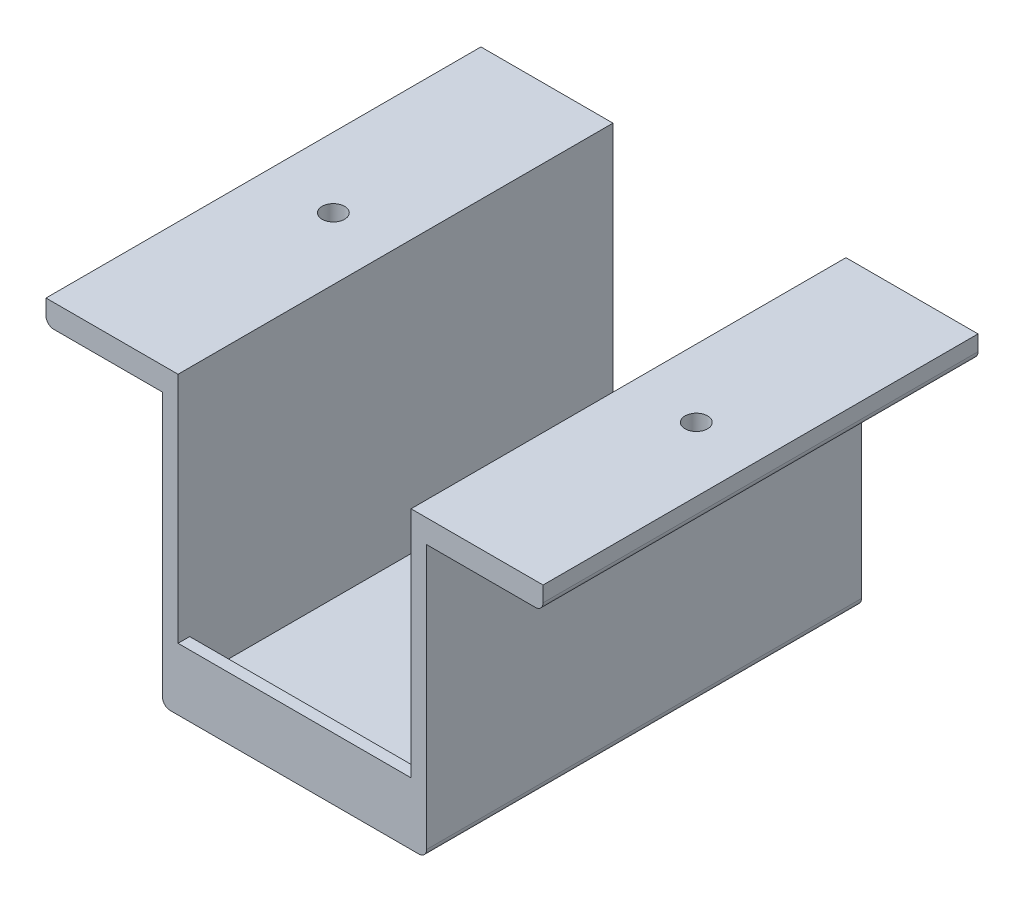
SolidWorks part; units mm, degrees
material "ABS"
ref_plane "Front Plane" through (0, 0, 0) normal (0, 0, 1) x (1, 0, 0)
ref_plane "Top Plane" through (0, 0, 0) normal (0, 1, 0) x (1, 0, 0)
ref_plane "Right Plane" through (0, 0, 0) normal (1, 0, 0) x (0, 0, -1)
sketch "Sketch2" plane through (0, 0, 0) normal (0, 1, 0) x (1, 0, 0)
  line L1 (0, 40.8875) -> (34, 40.8875)
  line L2 (0, 40.8875) -> (0, -15.1125)
  line L3 (0, -15.1125) -> (34, -15.1125)
  line L4 (34, 40.8875) -> (34, -15.1125)
  dimension "D1" = 34
  dimension "D2" = 56
extrude "Boss-Extrude1" add sketch "Sketch2" along normal blind 3
sketch "Sketch3" plane through (0, 3, 0) normal (0, 1, 0) x (1, 0, 0)
  line L0 (34, -15.1125) -> (34, 40.8875) construction
  line L1 (0, 40.8875) -> (2, 40.8875)
  line L2 (0, 40.8875) -> (0, -15.1125)
  line L3 (0, -15.1125) -> (2, -15.1125)
  line L4 (2, 40.8875) -> (2, -15.1125)
  line L13 (34, 40.8875) -> (32, 40.8875)
  line L14 (34, 40.8875) -> (34, -15.1125)
  line L15 (34, -15.1125) -> (32, -15.1125)
  line L16 (32, 40.8875) -> (32, -15.1125)
  dimension "D1" = 2
  dimension "D2" = 2
  dimension "D3" = 56
  dimension "D4" = 0
extrude "Boss-Extrude2" add sketch "Sketch3" along normal blind 35
sketch "Sketch4" plane through (34, 0, 0) normal (1, 0, 0) x (0, 0, -1)
  line L0 (-15.1125, 38) -> (40.8875, 38) construction
  line L1 (-15.1125, 38) -> (40.8875, 38)
  line L2 (-15.1125, 38) -> (-15.1125, 35.0081)
  line L3 (-15.1125, 35.0081) -> (40.8875, 35.0081)
  line L4 (40.8875, 38) -> (40.8875, 35.0081)
  dimension "D1" = 0
  dimension "D2" = 56
extrude "Boss-Extrude3" add sketch "Sketch4" along normal blind 15
sketch "Sketch5" plane through (0, 0, 0) normal (-1, 0, 0) x (0, 0, 1)
  line L0 (-40.8875, 38) -> (15.1125, 38) construction
  line L1 (-40.8875, 38) -> (15.1125, 38)
  line L2 (-40.8875, 38) -> (-40.8875, 35.0081)
  line L3 (-40.8875, 35.0081) -> (15.1125, 35.0081)
  line L4 (15.1125, 38) -> (15.1125, 35.0081)
  line L5 (-40.8875, 38) -> (-40.8875, 0) construction
  dimension "D1" = 0
  dimension "D2" = 56
  dimension "D3" = 0
extrude "Boss-Extrude4" add sketch "Sketch5" along normal blind 15
sketch "Sketch6" plane through (0, 3, 0) normal (0, 1, 0) x (1, 0, 0)
  line L0 (32, 40.8875) -> (2, 40.8875) construction
  line L5 (32, 40.8875) -> (2, 40.8875)
  line L6 (32, 40.8875) -> (32, 38.8875)
  line L7 (32, 38.8875) -> (2, 38.8875)
  line L8 (2, 40.8875) -> (2, 38.8875)
  line L10 (2, -13.6125) -> (32, -13.6125)
  line L11 (2, -13.6125) -> (2, -15.1125)
  line L12 (2, -15.1125) -> (32, -15.1125)
  line L13 (32, -13.6125) -> (32, -15.1125)
  dimension "D1" = 30
  dimension "D2" = 0
  dimension "D3" = 2
  dimension "D4" = 1.5
extrude "Boss-Extrude5" add sketch "Sketch6" along normal blind 5
sketch "Sketch8" plane through (0, 38, 0) normal (0, 1, 0) x (1, 0, 0)
  line L0 (49, 40.8875) -> (49, -15.1125) construction
  line L1 (-15, -15.1125) -> (-6.0021, -15.1125) construction
  line L2 (-15, -15.1125) -> (-15, 12.8875) construction
  line L3 (-15, 12.8875) -> (-6.0021, 12.8875) construction
  line L4 (-6.0021, -15.1125) -> (-6.0021, 12.8875) construction
  line L5 (49, -15.1125) -> (40.7304, -15.1125) construction
  line L6 (49, -15.1125) -> (49, 12.8875) construction
  line L7 (49, 12.8875) -> (40.7304, 12.8875) construction
  line L8 (40.7304, -15.1125) -> (40.7304, 12.8875) construction
  circle A0 centre (-6.0021, 12.8875) radius 1.45
  circle A1 centre (40.7304, 12.8875) radius 1.45
  dimension "D1" = 2.9
  dimension "D2" = 2.9
  dimension "D3" = 28
  dimension "D4" = 8.9979
  dimension "D5" = 28
  dimension "D6" = 0
extrude "Cut-Extrude1" cut sketch "Sketch8" against normal through all
fillet "Fillet1" radius 1 4 edges at (49, 35.0081, -12.8875) (-15, 35.0081, -12.8875) (34, 0, -12.8875) (0, 0, -12.8875)
